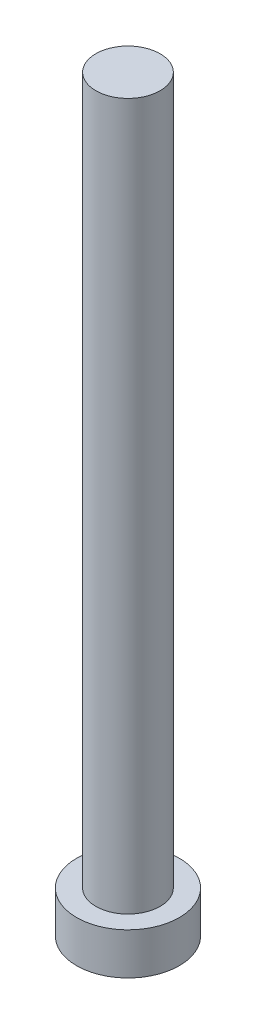
SolidWorks part; units mm, degrees
ref_plane "前视基准面" through (0, 0, 0) normal (0, 0, 1) x (1, 0, 0)
ref_plane "上视基准面" through (0, 0, 0) normal (0, 1, 0) x (1, 0, 0)
ref_plane "右视基准面" through (0, 0, 0) normal (1, 0, 0) x (0, 0, -1)
other "Configuration Table"
sketch "草图1" plane through (0, 0, 0) normal (0, 1, 0) x (1, 0, 0)
  circle A0 centre (0, 0) radius 1.6
  dimension "D1" = 3.2
extrude "凸台-拉伸1" add sketch "草图1" along normal blind 1.3
sketch "草图2" plane through (0, 0, 0) normal (0, 1, 0) x (1, 0, 0)
  circle A0 centre (0, 0) radius 1
extrude "凸台-拉伸2" add sketch "草图2" along normal blind 22 from surface at 1.3 starting at face at (0, 1.3, 1.6)
